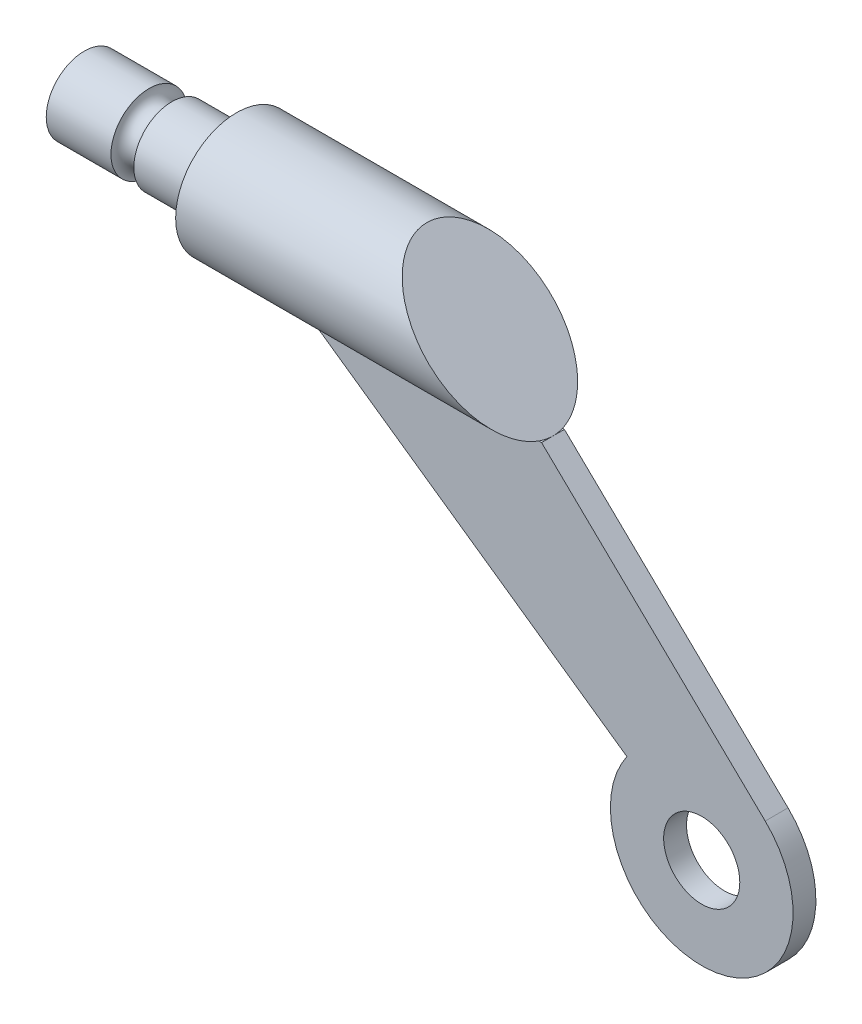
SolidWorks part; units mm, degrees
ref_plane "前视基准面" through (0, 0, 0) normal (0, 0, 1) x (1, 0, 0)
ref_plane "上视基准面" through (0, 0, 0) normal (0, 1, 0) x (1, 0, 0)
ref_plane "右视基准面" through (0, 0, 0) normal (1, 0, 0) x (0, 0, -1)
other "Configuration Table"
sketch "草图1" plane through (0, 0, 0) normal (0, 0, 1) x (1, 0, 0)
  line L0 (-114.7039, 45) -> (19.7969, 45) construction
  line L1 (-82.6084, 45) -> (-82.6084, 50)
  line L2 (-82.6084, 50) -> (-74.1035, 50)
  line L3 (-71.1035, 50) -> (-62.6084, 50)
  line L4 (-62.6084, 50) -> (-62.6084, 53)
  line L5 (-62.6084, 53) -> (-20.8715, 53)
  line L6 (-37.6084, 53) -> (8.3359, 8.6321) construction
  line L7 (-82.6084, 45) -> (-20.8715, 45)
  line L9 (-20.8715, 45) -> (-20.8715, 53)
  circle A1 centre (0, 0) radius 12 construction
  circle A2 centre (0, 0) radius 5 construction
  arc A3 (-74.1035, 50) -> (-71.1035, 50) centre (-72.6035, 50) ccw
  point P11 (0, 0)
  point P17 (0, 0)
  point P18 (0, 0)
  dimension "D4" = 3
  dimension "D9" = 24
  dimension "D10" = 10
  dimension "D1" = 45
  dimension "D2" = 10
  dimension "D3" = 20
  dimension "D5" = 10.0049
  dimension "D6" = 45
  dimension "D7" = 136
  dimension "D8" = 16
revolve "旋转1" add sketch "草图1" angle 360 about L0
sketch "草图2" plane through (0, 0, 0) normal (0, 0, 1) x (1, 0, 0)
  line L0 (-37.6084, 53) -> (8.3359, 8.6321)
extrude "切除-拉伸1" cut sketch "草图2" against normal through all and the other way through all
sketch "草图3" plane through (0, 0, 0) normal (0, 0, 1) x (1, 0, 0)
  line L0 (-21.0399, 37) -> (8.3359, 8.6321)
  line L1 (-52.8415, 37) -> (-9.8298, 6.8829)
  line L2 (-62.6084, 37) -> (-21.0399, 37) construction
  line L3 (-52.8415, 37) -> (-21.0399, 37)
  circle A0 centre (0, 0) radius 5 construction
  circle A1 centre (0, 0) radius 12 construction
  circle A2 centre (0, 0) radius 5
  circle A3 centre (0, 0) radius 12
  dimension "D1" = 145
extrude "凸台-拉伸1" add sketch "草图3" along normal mid plane 3 separate body contours A3 L0 L3 L1 | A3 A2
hole_wizard "大小mm 暗销孔2" positions "草图6" profile "草图7" hole size "Ø1.0" standard "GB"
sketch "草图6" plane through (-82.6084, 0, 0) normal (-1, 0, 0) x (0, 0, 1)
  point P0 (0, 45)
sketch "草图7" plane through (-82.6084, 45, 0) normal (0, 1, 0) x (0, 0, 1)
  line L0 (0, 0) -> (0, 45)
  line L1 (0, 45) -> (2.5, 42.5)
  line L2 (2.5, 42.5) -> (2.5, 0)
  line L5 (2.5, 0) -> (0, 0)
  line L10 (0, 45) -> (-2.5, 42.5) construction
  line L11 (0, -6.35) -> (0, 107.95) construction
  dimension "孔直径" = 5
  dimension "孔深度" = 45
  dimension "导头角度" = 90
